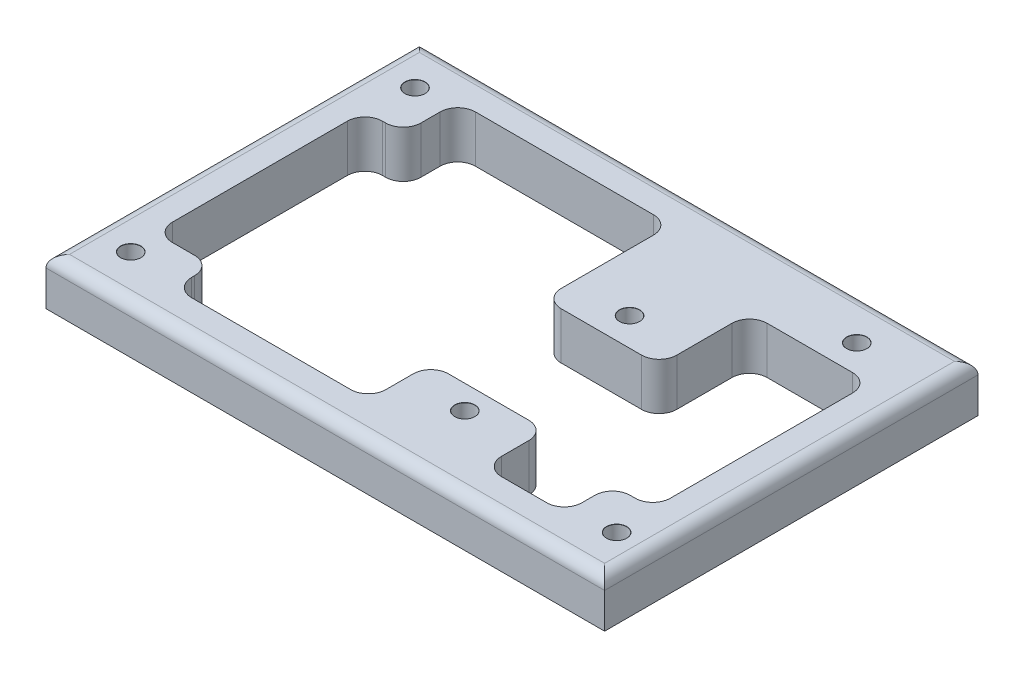
SolidWorks part; units mm, degrees
ref_plane "Front Plane" through (0, 0, 0) normal (0, 0, 1) x (1, 0, 0)
ref_plane "Top Plane" through (0, 0, 0) normal (0, 1, 0) x (1, 0, 0)
ref_plane "Right Plane" through (0, 0, 0) normal (1, 0, 0) x (0, 0, -1)
sketch "Sketch2" plane through (0, 0, 0) normal (0, 1, 0) x (1, 0, 0)
  line L1 (47.5, 31.75) -> (-47.5, 31.75)
  line L2 (47.5, 31.75) -> (47.5, -31.75)
  line L3 (47.5, -31.75) -> (-47.5, -31.75)
  line L4 (-47.5, 31.75) -> (-47.5, -31.75)
  line L5 (47.5, 31.75) -> (-47.5, -31.75) construction
  line L6 (47.5, -31.75) -> (-47.5, 31.75) construction
  point P0 (0, 0)
  dimension "D1" = 95
  dimension "D2" = 63.5
extrude "Boss-Extrude1" add sketch "Sketch2" along normal blind 8
hole_wizard "M3 Clearance Hole1" positions "Sketch7" profile "Sketch8" hole size "M3" standard "ANSI Metric" end condition through all
sketch "Sketch7" plane through (0, 8, 0) normal (0, 1, 0) x (1, 0, 0)
  line L1 (-40.6667, 24.17) -> (34.4633, 24.17)
  line L2 (-40.6667, 24.17) -> (-40.6667, -24.17)
  line L3 (-40.6667, -24.17) -> (34.4633, -24.17)
  line L4 (34.4633, 24.17) -> (34.4633, -24.17)
  line L5 (34.4633, -24.17) -> (41.9633, -24.17) construction
  line L12 (41.9633, -24.17) -> (47.5, -24.17) construction
  line L13 (47.5, -31.75) -> (47.5, 31.75) construction
  line L15 (0, 31.75) -> (0, 24.17) construction
  line L16 (47.5, 31.75) -> (-47.5, 31.75) construction
  line L17 (-3.1017, -24.17) -> (-3.1017, -31.75) construction
  line L18 (-47.5, -31.75) -> (47.5, -31.75) construction
  line L19 (11.1433, -19.17) -> (11.1433, -24.17) construction
  point P1 (-40.6667, 24.17)
  point P33 (-40.6667, -24.17)
  point P34 (34.4633, 24.17)
  point P43 (41.9633, -24.17)
  point P74 (11.1433, -19.17)
  point P80 (11.1433, 8.85)
  point P85 (-3.1017, -24.17)
  dimension "D1" = 48.34
  dimension "D2" = 75.13
  dimension "D3" = 7.5
  dimension "D4" = 51.81
  dimension "D5" = 5
  dimension "D6" = 28.02
sketch "Sketch8" plane through (-40.6667, 8, -24.17) normal (1, 0, 0) x (0, 0, 1)
  line L0 (0, 0) -> (0, 8)
  line L1 (0, 8) -> (1.7, 8)
  line L2 (1.7, 8) -> (1.7, 0.025)
  line L3 (1.7, 0.025) -> (1.725, 0)
  line L5 (1.725, 0) -> (0, 0)
  line L6 (-1.7, 0.025) -> (-1.725, 0) construction
  line L11 (0, -6.35) -> (0, 107.95) construction
  dimension "Thru Hole Dia." = 3.4
  dimension "Thru Hole Depth" = 8
  dimension "Near C'Sink Dia." = 3.45
  dimension "Near C'Sink Angle" = 90
sketch "Sketch9" plane through (0, 8, 0) normal (0, 1, 0) x (1, 0, 0)
  line L0 (-34.9742, 19.4874) -> (-34.9742, 22.75)
  line L2 (-37.9742, 16.4874) -> (-38.5, 16.4874)
  line L3 (-41.5, 13.4874) -> (-41.5, -16.2525)
  line L4 (-38.5, -19.2525) -> (-34.7301, -19.2525)
  line L5 (-31.7301, -22.2525) -> (-31.7301, -22.75)
  line L6 (-31.9742, 25.75) -> (-1.6848, 25.75)
  line L7 (-28.7301, -25.75) -> (-1.6848, -25.75)
  line L8 (1.3152, -22.75) -> (1.3152, -18.118)
  line L9 (4.3152, -15.118) -> (17.9713, -15.118)
  line L10 (20.9713, -18.118) -> (20.9713, -22.75)
  line L11 (23.9713, -25.75) -> (31.6479, -25.75)
  line L12 (34.6479, -22.75) -> (34.6479, -20.5605)
  line L13 (37.6479, -17.5605) -> (38.5, -17.5605)
  line L14 (41.5, -14.5605) -> (41.5, 16.4283)
  line L15 (38.5, 19.4283) -> (23.9713, 19.4283)
  line L16 (20.9713, 16.4283) -> (20.9713, 7.055)
  line L17 (17.9713, 4.055) -> (4.3152, 4.055)
  line L18 (1.3152, 7.055) -> (1.3152, 22.75)
  line L19 (-47.5, 31.75) -> (-47.5, -31.75) construction
  line L20 (47.5, 31.75) -> (-47.5, 31.75) construction
  line L21 (47.5, -31.75) -> (47.5, 31.75) construction
  line L22 (-47.5, -31.75) -> (47.5, -31.75) construction
  circle A0 centre (41.9633, -24.17) radius 1.725 construction
  circle A1 centre (34.4633, 24.17) radius 1.725 construction
  circle A2 centre (11.1433, 8.85) radius 1.725 construction
  circle A3 centre (11.1433, -19.17) radius 1.725 construction
  circle A4 centre (-40.6667, -24.17) radius 1.725 construction
  circle A5 centre (-40.6667, 24.17) radius 1.725 construction
  circle A6 centre (41.9633, -24.17) radius 1.725 construction
  circle A7 centre (34.4633, 24.17) radius 1.725 construction
  circle A8 centre (11.1433, 8.85) radius 1.725 construction
  circle A9 centre (11.1433, -19.17) radius 1.725 construction
  circle A10 centre (-40.6667, -24.17) radius 1.725 construction
  circle A11 centre (-40.6667, 24.17) radius 1.725 construction
  arc A12 (-34.9742, 22.75) -> (-31.9742, 25.75) centre (-31.9742, 22.75) cw
  arc A13 (-1.6848, 25.75) -> (1.3152, 22.75) centre (-1.6848, 22.75) cw
  arc A14 (4.3152, 4.055) -> (1.3152, 7.055) centre (4.3152, 7.055) cw
  arc A15 (20.9713, 7.055) -> (17.9713, 4.055) centre (17.9713, 7.055) cw
  arc A16 (23.9713, 19.4283) -> (20.9713, 16.4283) centre (23.9713, 16.4283) ccw
  arc A17 (41.5, 16.4283) -> (38.5, 19.4283) centre (38.5, 16.4283) ccw
  arc A18 (38.5, -17.5605) -> (41.5, -14.5605) centre (38.5, -14.5605) ccw
  arc A19 (34.6479, -20.5605) -> (37.6479, -17.5605) centre (37.6479, -20.5605) cw
  arc A20 (31.6479, -25.75) -> (34.6479, -22.75) centre (31.6479, -22.75) ccw
  arc A21 (20.9713, -22.75) -> (23.9713, -25.75) centre (23.9713, -22.75) ccw
  arc A22 (17.9713, -15.118) -> (20.9713, -18.118) centre (17.9713, -18.118) cw
  arc A23 (1.3152, -18.118) -> (4.3152, -15.118) centre (4.3152, -18.118) cw
  arc A24 (-1.6848, -25.75) -> (1.3152, -22.75) centre (-1.6848, -22.75) ccw
  arc A25 (-31.7301, -22.75) -> (-28.7301, -25.75) centre (-28.7301, -22.75) ccw
  arc A26 (-34.7301, -19.2525) -> (-31.7301, -22.2525) centre (-34.7301, -22.2525) cw
  arc A27 (-41.5, -16.2525) -> (-38.5, -19.2525) centre (-38.5, -16.2525) ccw
  arc A28 (-38.5, 16.4874) -> (-41.5, 13.4874) centre (-38.5, 13.4874) ccw
  arc A29 (-34.9742, 19.4874) -> (-37.9742, 16.4874) centre (-37.9742, 19.4874) cw
  point P36 (0, 0)
  point P37 (11.1433, -15.118)
  point P38 (0, 0)
  point P39 (11.1433, 4.055)
  dimension "D5" = 3
  dimension "D1" = 6
  dimension "D2" = 6
  dimension "D3" = 6
  dimension "D4" = 6
extrude "Cut-Extrude1" cut sketch "Sketch9" against normal blind 10
sketch "Sketch10" plane through (0, 0, 0) normal (0, -1, 0) x (1, 0, 0)
  line L1 (-41.4017, 20.903) -> (-38.2049, 21.9)
  line L2 (-38.2049, 21.9) -> (-37.47, 25.167)
  line L3 (-37.47, 25.167) -> (-39.9318, 27.437)
  line L4 (-39.9318, 27.437) -> (-43.1285, 26.44)
  line L5 (-43.1285, 26.44) -> (-43.8635, 23.173)
  line L6 (-43.8635, 23.173) -> (-41.4017, 20.903)
  line L7 (-41.9734, -27.2532) -> (-38.65, -26.8432)
  line L8 (-38.65, -26.8432) -> (-37.3433, -23.76)
  line L9 (-37.3433, -23.76) -> (-39.3601, -21.0868)
  line L10 (-39.3601, -21.0868) -> (-42.6835, -21.4968)
  line L11 (-42.6835, -21.4968) -> (-43.9902, -24.58)
  line L12 (-43.9902, -24.58) -> (-41.9734, -27.2532)
  line L13 (8.0727, -10.1861) -> (10.7651, -12.1772)
  line L14 (10.7651, -12.1772) -> (13.8356, -10.8411)
  line L15 (13.8356, -10.8411) -> (14.2138, -7.5139)
  line L16 (14.2138, -7.5139) -> (11.5215, -5.5228)
  line L17 (11.5215, -5.5228) -> (8.4509, -6.8589)
  line L18 (8.4509, -6.8589) -> (8.0727, -10.1861)
  line L19 (8.0802, 17.8169) -> (10.7835, 15.8407)
  line L20 (10.7835, 15.8407) -> (13.8466, 17.1938)
  line L21 (13.8466, 17.1938) -> (14.2064, 20.5231)
  line L22 (14.2064, 20.5231) -> (11.503, 22.4993)
  line L23 (11.503, 22.4993) -> (8.4399, 21.1462)
  line L24 (8.4399, 21.1462) -> (8.0802, 17.8169)
  line L25 (32.6053, -26.9559) -> (35.9469, -27.172)
  line L26 (35.9469, -27.172) -> (37.8049, -24.3861)
  line L27 (37.8049, -24.3861) -> (36.3212, -21.3841)
  line L28 (36.3212, -21.3841) -> (32.9796, -21.168)
  line L29 (32.9796, -21.168) -> (31.1216, -23.9539)
  line L30 (31.1216, -23.9539) -> (32.6053, -26.9559)
  line L31 (40.0405, 21.4284) -> (43.3761, 21.134)
  line L32 (43.3761, 21.134) -> (45.2989, 23.8756)
  line L33 (45.2989, 23.8756) -> (43.8861, 26.9116)
  line L34 (43.8861, 26.9116) -> (40.5504, 27.206)
  line L35 (40.5504, 27.206) -> (38.6276, 24.4644)
  line L36 (38.6276, 24.4644) -> (40.0405, 21.4284)
  circle A0 centre (34.4633, -24.17) radius 1.7 construction
  circle A1 centre (41.9633, 24.17) radius 1.7 construction
  circle A2 centre (11.1433, 19.17) radius 1.7 construction
  circle A3 centre (11.1433, -8.85) radius 1.7 construction
  circle A4 centre (-40.6667, -24.17) radius 1.7 construction
  circle A5 centre (-40.6667, 24.17) radius 1.7 construction
  circle A6 centre (34.4633, -24.17) radius 1.7 construction
  circle A7 centre (41.9633, 24.17) radius 1.7 construction
  circle A8 centre (11.1433, 19.17) radius 1.7 construction
  circle A9 centre (11.1433, -8.85) radius 1.7 construction
  circle A10 centre (-40.6667, -24.17) radius 1.7 construction
  circle A11 centre (-40.6667, 24.17) radius 1.7 construction
  circle A12 centre (-40.6667, 24.17) radius 2.9 construction
  circle A13 centre (-40.6667, -24.17) radius 2.9 construction
  circle A14 centre (11.1433, -8.85) radius 2.9 construction
  circle A15 centre (11.1433, 19.17) radius 2.9 construction
  circle A16 centre (34.4633, -24.17) radius 2.9 construction
  circle A17 centre (41.9633, 24.17) radius 2.9 construction
  dimension "D1" = 5.8
extrude "Cut-Extrude2" cut sketch "Sketch10" against normal blind 2.4
fillet "Fillet2" radius 2 4 edges at (0, 8, -31.75) (47.5, 8, 0) (0, 8, 31.75) (-47.5, 8, 0)
